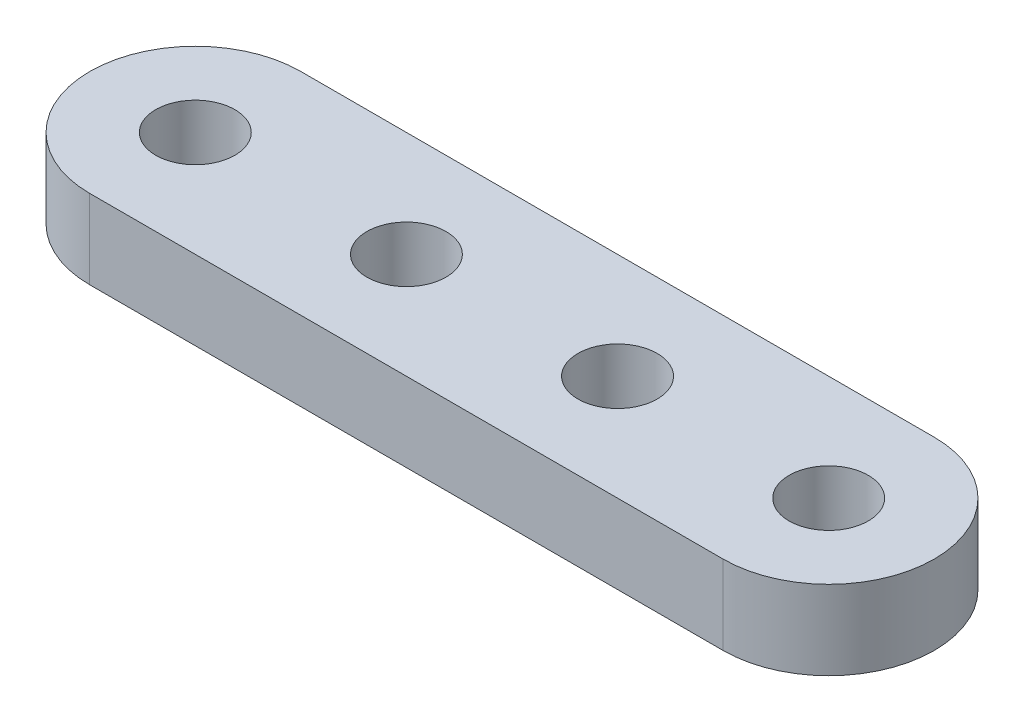
SolidWorks part; units mm, degrees
ref_plane "Front Plane" through (0, 0, 0) normal (0, 0, 1) x (1, 0, 0)
ref_plane "Top Plane" through (0, 0, 0) normal (0, 1, 0) x (1, 0, 0)
ref_plane "Right Plane" through (0, 0, 0) normal (1, 0, 0) x (0, 0, -1)
sketch "Sketch2" plane through (0, 0, 0) normal (0, 1, 0) x (1, 0, 0)
  line L0 (0, 0) -> (24, 0) construction
  line L1 (0, 4) -> (24, 4)
  line L2 (0, -4) -> (24, -4)
  arc A0 (0, 4) -> (0, -4) centre (0, 0) ccw
  arc A1 (24, -4) -> (24, 4) centre (24, 0) ccw
  circle A2 centre (0, 0) radius 1.5
  circle A3 centre (8, 0) radius 1.5
  circle A4 centre (16, 0) radius 1.5
  circle A5 centre (24, 0) radius 1.5
  point P3 (12, 0)
  dimension "D1" = 3
  dimension "D2" = 8
  dimension "D3" = 24
  dimension "D4" = 4
extrude "Boss-Extrude2" add sketch "Sketch2" along normal blind 3
